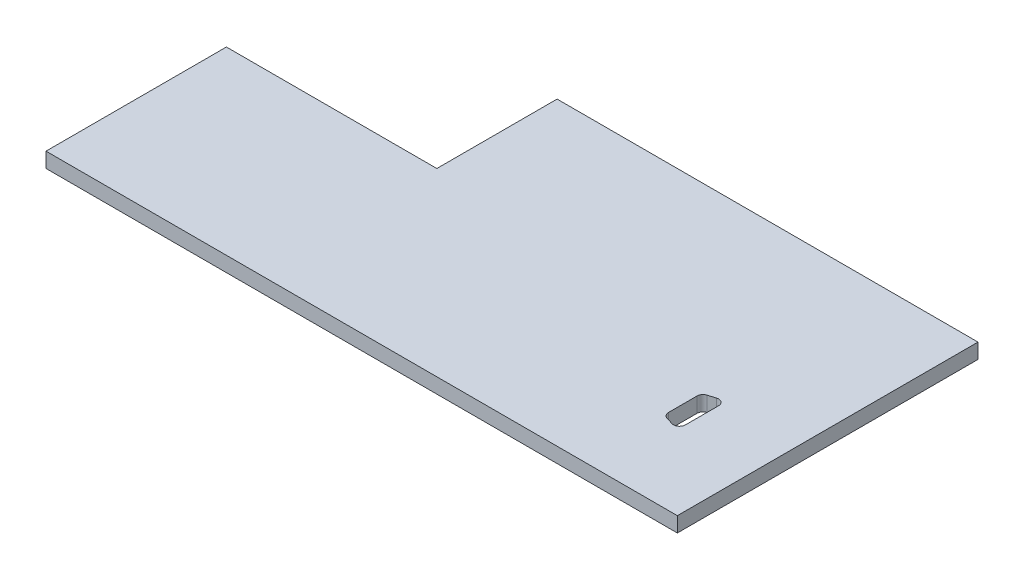
SolidWorks part; units mm, degrees
ref_plane "Front Plane" through (0, 0, 0) normal (0, 0, 1) x (1, 0, 0)
ref_plane "Top Plane" through (0, 0, 0) normal (0, 1, 0) x (1, 0, 0)
ref_plane "Right Plane" through (0, 0, 0) normal (1, 0, 0) x (0, 0, -1)
sketch "Sketch1" plane through (0, 0, 0) normal (0, 1, 0) x (1, 0, 0)
  line L0 (0, 0) -> (0, 76.2)
  line L3 (0, 76.2) -> (88.9, 76.2)
  line L4 (88.9, 76.2) -> (88.9, 127)
  line L5 (88.9, 127) -> (266.7, 127)
  line L6 (266.7, 127) -> (266.7, 0)
  line L7 (266.7, 0) -> (0, 0)
  dimension "D2" = 266.7
  dimension "D3" = 177.8
  dimension "D4" = 88.9
  dimension "D6" = 50.8
  dimension "D7" = 127
extrude "Boss-Extrude1" add sketch "Sketch1" along normal blind 6.35
sketch "Sketch2" plane through (0, 6.35, 0) normal (0, 1, 0) x (1, 0, 0)
  line L0 (19.05, 63.5) -> (101.6, 63.5)
  line L1 (101.6, 63.5) -> (101.6, 107.95)
  line L2 (19.05, 63.5) -> (19.05, 76.2)
  line L3 (88.9, 76.2) -> (0, 76.2) construction
  line L4 (19.05, 76.2) -> (88.9, 76.2)
  line L5 (88.9, 76.2) -> (88.9, 107.95)
  line L6 (88.9, 107.95) -> (101.6, 107.95)
  line L10 (88.9, 127) -> (88.9, 76.2) construction
  line L11 (88.9, 76.2) -> (0, 76.2) construction
  line L14 (0, 76.2) -> (0, 0) construction
  line L15 (266.7, 127) -> (88.9, 127) construction
  dimension "D1" = 19.05
  dimension "D2" = 19.05
  dimension "D5" = 12.7
  dimension "D6" = 12.7
extrude "Boss-Extrude2" add sketch "Sketch2" against normal blind 11.43
sketch "Sketch3" plane through (0, 6.35, 0) normal (0, 1, 0) x (1, 0, 0)
  line L0 (235.204, 31.496) -> (235.204, 52.324)
  line L1 (235.204, 52.324) -> (227.076, 49.784)
  line L2 (227.076, 49.784) -> (227.076, 34.036)
  line L3 (227.076, 34.036) -> (235.204, 31.496)
  line L4 (0, 0) -> (266.7, 0) construction
  line L5 (266.7, 0) -> (266.7, 127) construction
  dimension "D1" = 31.496
  dimension "D2" = 31.496
  dimension "D3" = 20.828
  dimension "D4" = 15.748
  dimension "D5" = 2.54
  dimension "D6" = 8.128
extrude "Cut-Extrude1" cut sketch "Sketch3" against normal blind 12.7
fillet "Fillet1" radius 2.54 4 edges at (235.204, 3.175, -31.496) (227.076, 3.175, -34.036) (235.204, 3.175, -52.324) (227.076, 3.175, -49.784)
